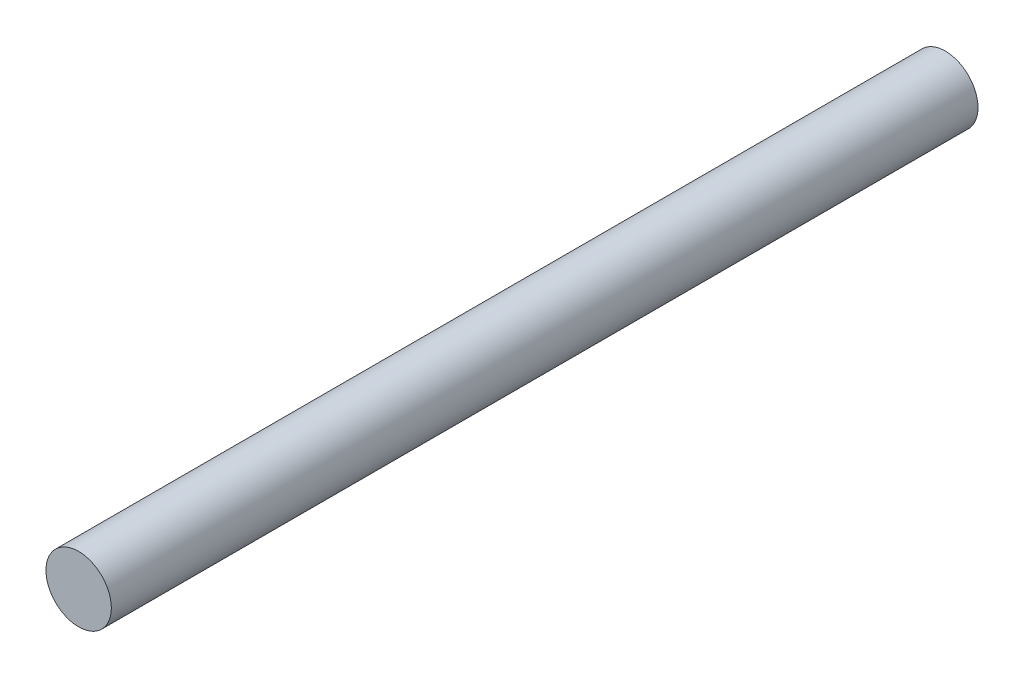
SolidWorks part; units mm, degrees
ref_plane "Plan de face" through (0, 0, 0) normal (0, 0, 1) x (1, 0, 0)
ref_plane "Plan de dessus" through (0, 0, 0) normal (0, 1, 0) x (1, 0, 0)
ref_plane "Plan de droite" through (0, 0, 0) normal (1, 0, 0) x (0, 0, -1)
sketch "Esquisse1" plane through (0, 0, 0) normal (0, 0, 1) x (1, 0, 0)
  circle A0 centre (0, 0) radius 4
  dimension "D1" = 8
extrude "Boss.-Extru.1" add sketch "Esquisse1" along normal blind 106
